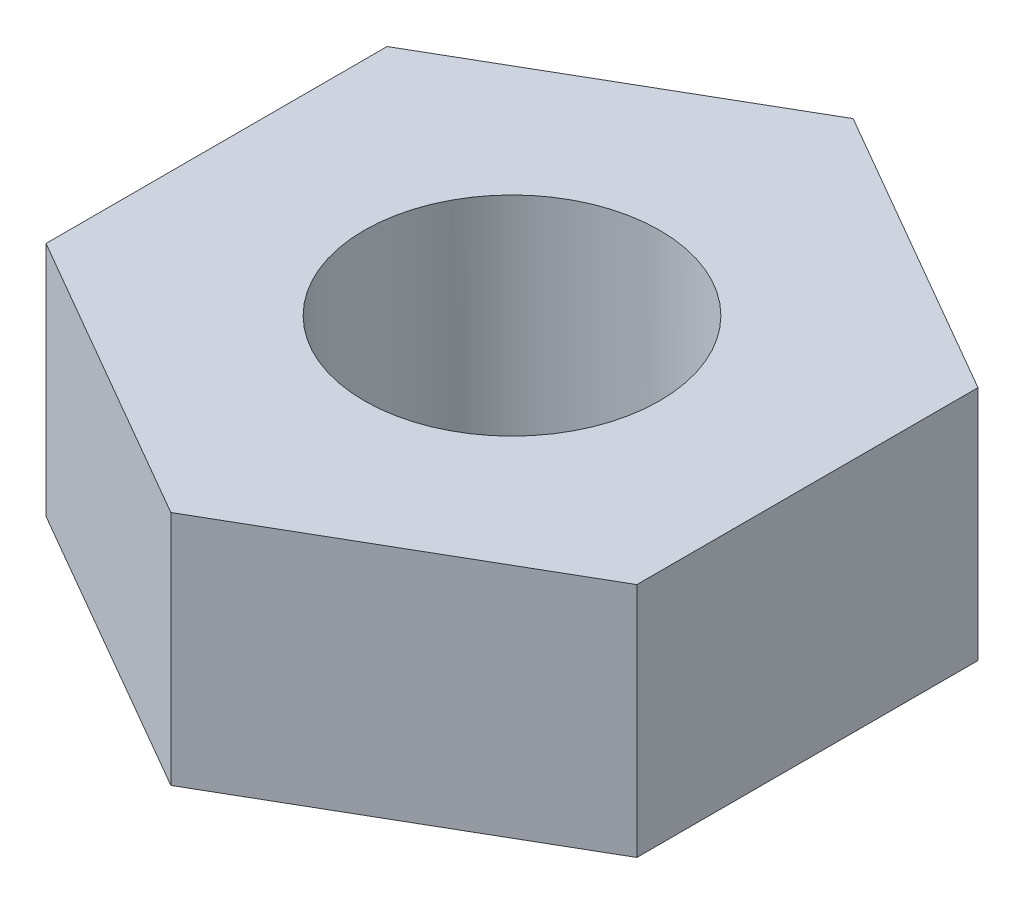
SolidWorks part; units mm, degrees
ref_plane "Front Plane" through (0, 0, 0) normal (0, 0, 1) x (1, 0, 0)
ref_plane "Top Plane" through (0, 0, 0) normal (0, 1, 0) x (1, 0, 0)
ref_plane "Right Plane" through (0, 0, 0) normal (1, 0, 0) x (0, 0, -1)
sketch "Sketch1" plane through (0, 0, 0) normal (0, 1, 0) x (1, 0, 0)
  line L0 (2, -1.1547) -> (0, -2.3094)
  line L1 (0, -2.3094) -> (-2, -1.1547)
  line L2 (-2, -1.1547) -> (-2, 1.1547)
  line L3 (-2, 1.1547) -> (0, 2.3094)
  line L4 (0, 2.3094) -> (2, 1.1547)
  line L5 (2, 1.1547) -> (2, -1.1547)
extrude "Boss-Extrude1" add sketch "Sketch1" against normal blind 1.6
sketch "Sketch2" plane through (0, 0, 0) normal (0, 1, 0) x (1, 0, 0)
  circle A0 centre (0, 0) radius 1
extrude "Cut-Extrude1" cut sketch "Sketch2" against normal through all and the other way through all
cosmetic thread "Cosmetic Thread1"
